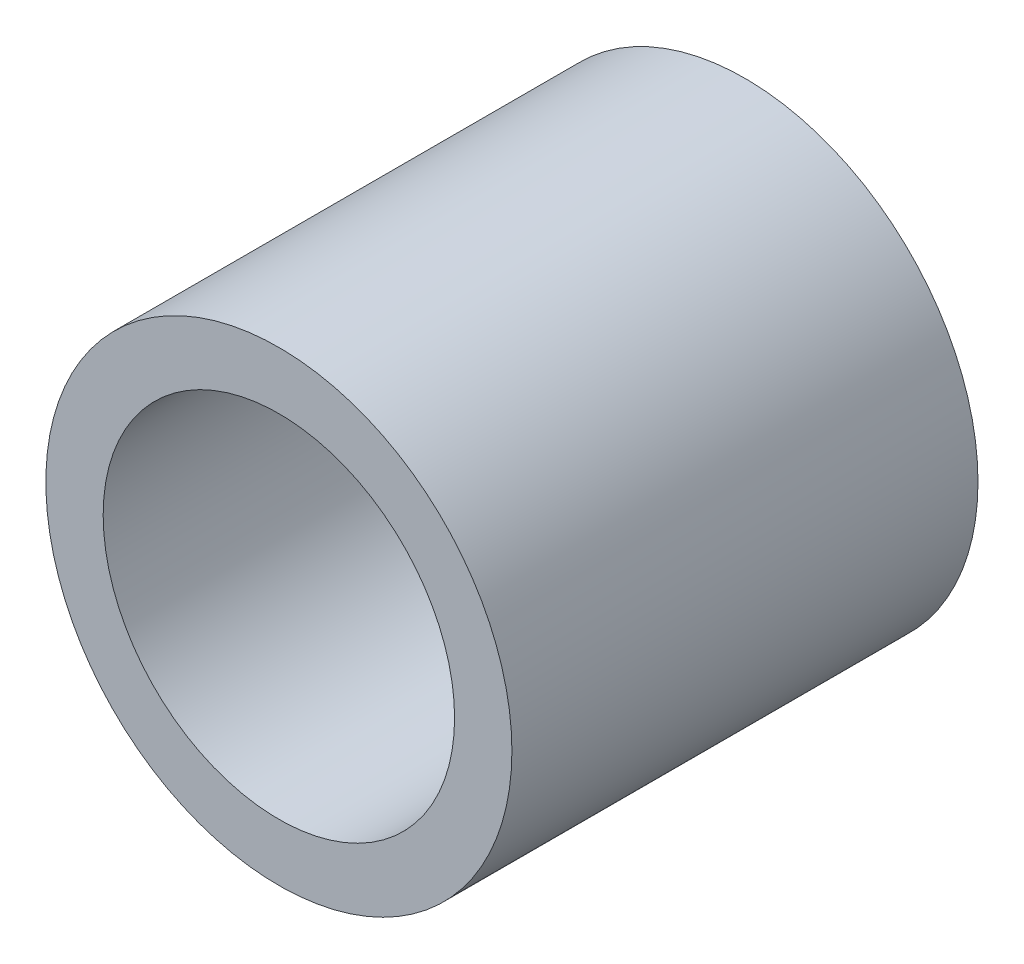
SolidWorks part; units mm, degrees
ref_plane "Front Plane" through (0, 0, 0) normal (0, 0, 1) x (1, 0, 0)
ref_plane "Top Plane" through (0, 0, 0) normal (0, 1, 0) x (1, 0, 0)
ref_plane "Right Plane" through (0, 0, 0) normal (1, 0, 0) x (0, 0, -1)
sketch "Sketch1" plane through (0, 0, 0) normal (0, 0, 1) x (1, 0, 0)
  circle A0 centre (0, 0) radius 6.35
  circle A1 centre (0, 0) radius 4.7879
  dimension "D1" = 12.7
  dimension "ID" = 9.5758
extrude "Extrude1" add sketch "Sketch1" along normal mid plane 12.7
sketch "Sketch2" plane through (0, 0, 0) normal (1, 0, 0) x (0, 0, -1)
  line L0 (-6.35, -4.7879) -> (6.35, -4.7879) construction
  line L3 (6.35, 4.7879) -> (-6.35, 4.7879) construction
  line L5 (-6.35, -4.7879) -> (6.35, -4.7879)
  line L6 (6.35, 4.7879) -> (-6.35, 4.7879)
sketch "Sketch4" plane through (0, 0, 6.35) normal (0, 0, 1) x (1, 0, 0)
  line L0 (0, 0) -> (-3.3856, 3.3856)
  line L1 (0, -17.4625) -> (0, 17.4625) construction
  circle A0 centre (0, 0) radius 4.7879 construction
  dimension "D1" = 45
